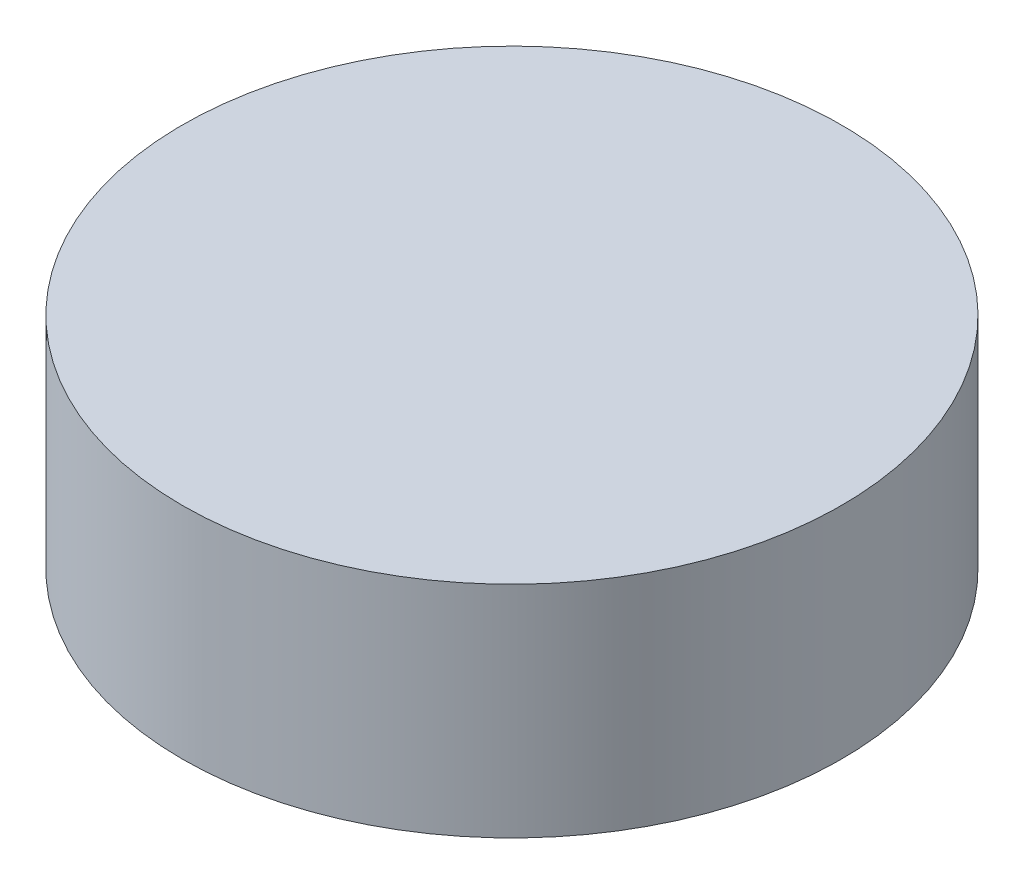
SolidWorks part; units mm, degrees
ref_plane "Front Plane" through (0, 0, 0) normal (0, 0, 1) x (1, 0, 0)
ref_plane "Top Plane" through (0, 0, 0) normal (0, 1, 0) x (1, 0, 0)
ref_plane "Right Plane" through (0, 0, 0) normal (1, 0, 0) x (0, 0, -1)
sketch "Sketch1" plane through (0, 0, 0) normal (0, 1, 0) x (1, 0, 0)
  circle A0 centre (0, 0) radius 75
  dimension "D1" = 150
extrude "Boss-Extrude1" add sketch "Sketch1" along normal blind 50
